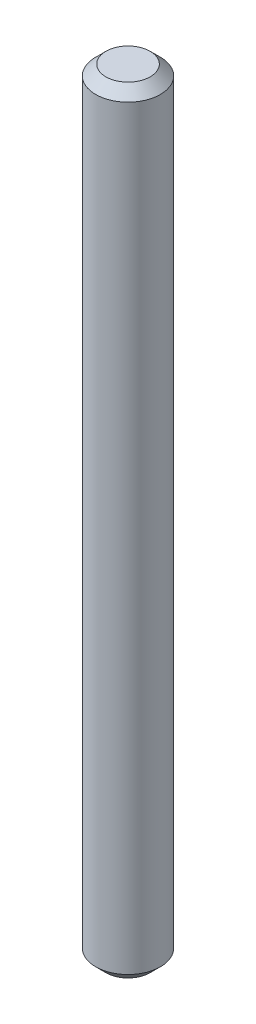
SolidWorks part; units mm, degrees
ref_plane "Front Plane" through (0, 0, 0) normal (0, 0, 1) x (1, 0, 0)
ref_plane "Top Plane" through (0, 0, 0) normal (0, 1, 0) x (1, 0, 0)
ref_plane "Right Plane" through (0, 0, 0) normal (1, 0, 0) x (0, 0, -1)
sketch "Sketch1" plane through (0, 0, 0) normal (0, 1, 0) x (1, 0, 0)
  circle A0 centre (0, 0) radius 3.175
  dimension "D1" = 6.35
extrude "Boss-Extrude1" add sketch "Sketch1" along normal blind 76.2
chamfer "Chamfer1" distance 1 angle 45 2 edges at (0, 76.2, 3.175) (0, 0, 3.175)
